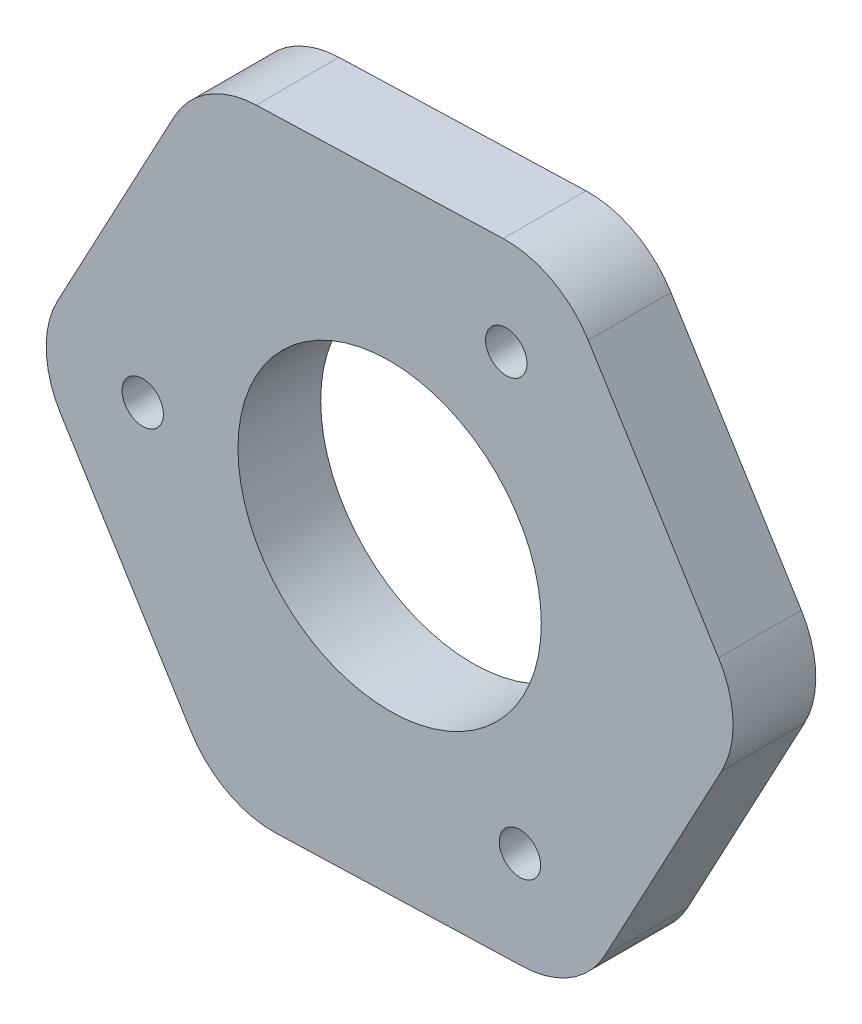
SolidWorks part; units mm, degrees
ref_plane "Front Plane" through (0, 0, 0) normal (0, 0, 1) x (1, 0, 0)
ref_plane "Top Plane" through (0, 0, 0) normal (0, 1, 0) x (1, 0, 0)
ref_plane "Right Plane" through (0, 0, 0) normal (1, 0, 0) x (0, 0, -1)
sketch "Sketch1" plane through (0, 0, 0) normal (0, 0, 1) x (1, 0, 0)
  line L6 (24.453, 353.9055) -> (33.9035, 338.6834)
  line L7 (40.0746, 335.3792) -> (57.9825, 335.9525)
  line L8 (63.9296, 339.6447) -> (72.387, 355.4401)
  line L9 (72.163, 362.4365) -> (62.7126, 377.6585)
  line L10 (56.5415, 380.9628) -> (38.6336, 380.3894)
  line L11 (32.6865, 376.6973) -> (24.229, 360.9019)
  circle A10 centre (57.7585, 342.9489) radius 1.5
  circle A11 centre (48.308, 358.171) radius 11
  circle A12 centre (56.7655, 373.9664) radius 1.5
  circle A13 centre (30.4001, 357.5976) radius 1.5
  arc A14 (33.9035, 338.6834) -> (40.0746, 335.3792) centre (39.8506, 342.3756) ccw
  arc A15 (57.9825, 335.9525) -> (63.9296, 339.6447) centre (57.7585, 342.9489) ccw
  arc A16 (72.387, 355.4401) -> (72.163, 362.4365) centre (66.216, 358.7443) ccw
  arc A17 (62.7126, 377.6585) -> (56.5415, 380.9628) centre (56.7655, 373.9664) ccw
  arc A18 (38.6336, 380.3894) -> (32.6865, 376.6973) centre (38.8576, 373.393) ccw
  arc A19 (24.229, 360.9019) -> (24.453, 353.9055) centre (30.4001, 357.5976) ccw
  point P5 (-4.6964, -12.7878)
  dimension "D11" = 7
  dimension "D17" = 3
  dimension "D20" = 22
  dimension "D1" = 335.3792
  dimension "D2" = 40.0746
  dimension "D3" = 333.9251
  dimension "D4" = 17.9171
  dimension "D5" = 60
  dimension "D6" = 60
  dimension "D7" = 60
  dimension "D8" = 60
  dimension "D9" = 60
  dimension "D10" = 60
  dimension "D12" = 7
  dimension "D13" = 7
  dimension "D14" = 7
  dimension "D15" = 7
  dimension "D16" = 7
  dimension "D18" = 22.5167
  dimension "D19" = 22.5167
extrude "Boss-Extrude1" add sketch "Sketch1" along normal blind 6 separate body
